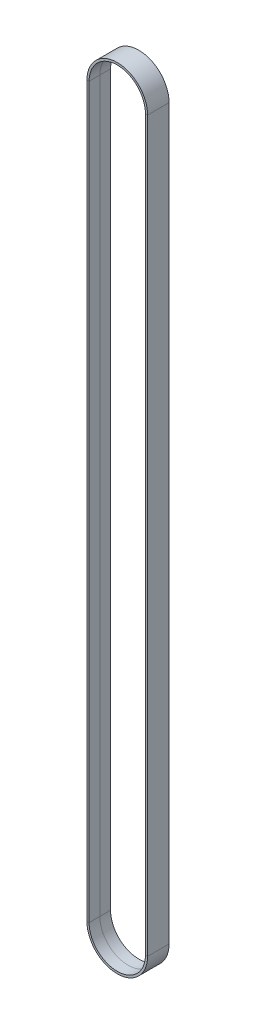
SolidWorks part; units mm, degrees
ref_plane "Спереди" through (0, 0, 0) normal (0, 0, 1) x (1, 0, 0)
ref_plane "Сверху" through (0, 0, 0) normal (0, 1, 0) x (1, 0, 0)
ref_plane "Справа" through (0, 0, 0) normal (1, 0, 0) x (0, 0, -1)
sketch "Эскиз2" plane through (0, 0, 0) normal (0, 0, 1) x (1, 0, 0)
  line L0 (0, 0) -> (1, 0) construction
  line L1 (0, 0) -> (0, 1) construction
  line L2 (26.25, 0) -> (26.25, -678.6787)
  line L3 (-26.25, -678.6787) -> (-26.25, 0)
  arc A0 (-26.25, 0) -> (26.25, 0) centre (0, 0) cw
  arc A1 (26.25, -678.6787) -> (-26.25, -678.6787) centre (0, -678.6787) cw
ref_plane "Плоскость1" through (0, 0, 0) normal (0, 0, 1) x (1, 0, 0)
sketch "Эскиз3" plane through (0, 0, 0) normal (0, 0, 1) x (1, 0, 0)
  line L0 (-26.25, -678.6787) -> (-26.25, 0) construction
  line L1 (26.25, 0) -> (26.25, -678.6787) construction
  line L2 (-26.25, -678.6787) -> (-26.25, 0)
  line L3 (26.25, 0) -> (26.25, -678.6787)
  arc A0 (-26.25, -678.6787) -> (26.25, -678.6787) centre (0, -678.6787) ccw construction
  arc A1 (26.25, 0) -> (-26.25, 0) centre (0, 0) ccw construction
  arc A2 (-26.25, -678.6787) -> (26.25, -678.6787) centre (0, -678.6787) ccw
  arc A3 (26.25, 0) -> (-26.25, 0) centre (0, 0) ccw
ref_plane "Плоскость2" through (0, 0, 0) normal (0, 1, 0) x (1, 0, 0)
sketch "Эскиз4" plane through (0, 0, 0) normal (0, 1, 0) x (1, 0, 0)
  line L2 (26.25, 0) -> (26.25, -10)
  line L3 (26.25, -10) -> (28.25, -10)
  line L6 (26.25, 0) -> (26.25, 10)
  line L7 (26.25, 10) -> (28.25, 10)
  line L10 (26.2494, -10) -> (22.8547, -10) construction
  line L11 (22.6195, 10) -> (25.7408, 10) construction
  line L12 (28.25, -10) -> (28.25, 10)
  dimension "D1" = 2
  dimension "D2" = 2
sweep "По траектории1" add profiles "Эскиз4" path "Эскиз3"
